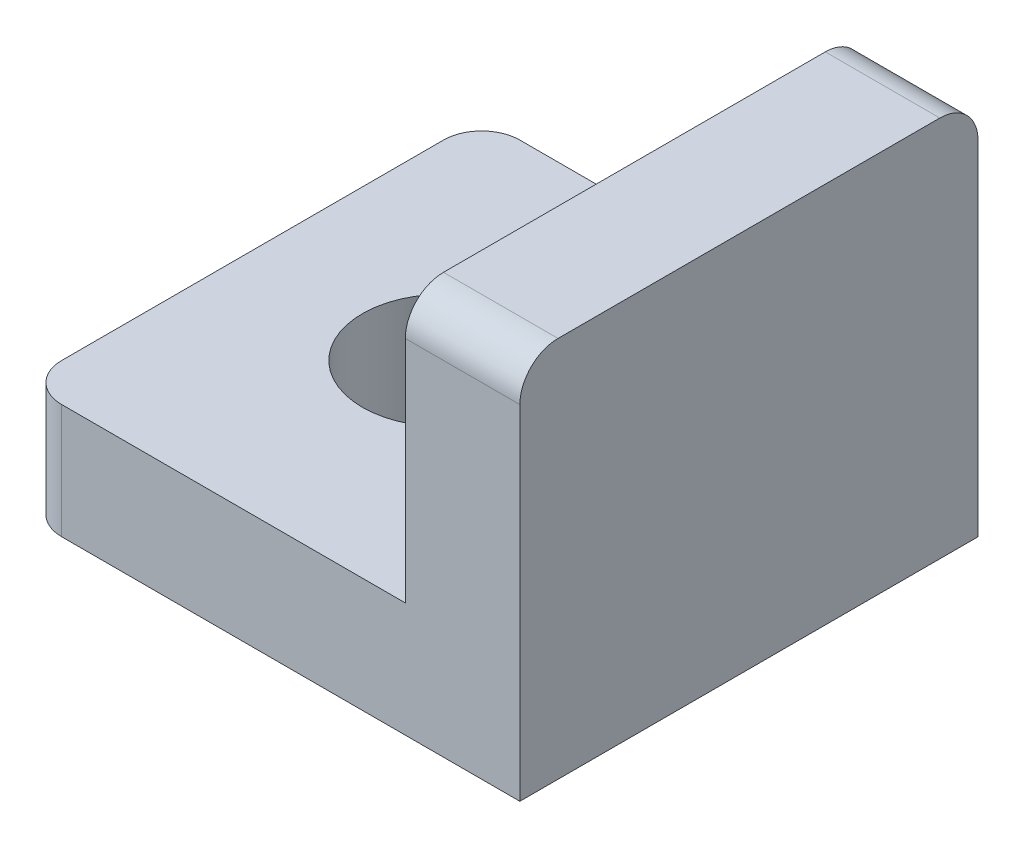
SolidWorks part; units mm, degrees
ref_plane "前基準面" through (0, 0, 0) normal (0, 0, 1) x (1, 0, 0)
ref_plane "上基準面" through (0, 0, 0) normal (0, 1, 0) x (1, 0, 0)
ref_plane "右基準面" through (0, 0, 0) normal (1, 0, 0) x (0, 0, -1)
sketch "草圖1" plane through (0, 0, 0) normal (0, 1, 0) x (1, 0, 0)
  line L1 (8, -6) -> (-5, -6)
  line L2 (8, -6) -> (8, 6)
  line L3 (8, 6) -> (-5, 6)
  line L4 (-5, -6) -> (-5, 6)
  line L5 (0, -5.5) -> (0, 5.5) construction
  line L6 (-5.5, 0) -> (5.5, 0) construction
  point P0 (0, 0)
  dimension "D1" = 5
  dimension "D2" = 12
  dimension "D3" = 8
  dimension "D4" = 6
extrude "填料-伸長1" add sketch "草圖1" along normal blind 10
shell "薄殼1" thickness 3
sketch "草圖2" plane through (0, 3, 0) normal (0, 1, 0) x (1, 0, 0)
  line L0 (0, -5.5) -> (0, 5.5) construction
  line L2 (-5.5, 0) -> (5.5, 0) construction
  circle A0 centre (0, 0) radius 2.125
  dimension "D1" = 4.25
extrude "除料-伸長1" cut sketch "草圖2" against normal through all
sketch "草圖3" plane through (5, 0, 0) normal (1, 0, 0) x (0, 0, -1)
  line L0 (0, 5.5) -> (0, -5.5) construction
  line L1 (7.15, 0) -> (-7.15, 0) construction
  circle A0 centre (0, 6.5) radius 2.625
  dimension "D1" = 5.25
  dimension "D2" = 6.5
extrude "除料-伸長4" cut sketch "草圖3" along normal blind 2.5
fillet "圓角1" radius 1 4 edges at (-5, 1.5, 6) (-5, 1.5, -6) (6.5, 10, -6) (6.5, 10, 6)
